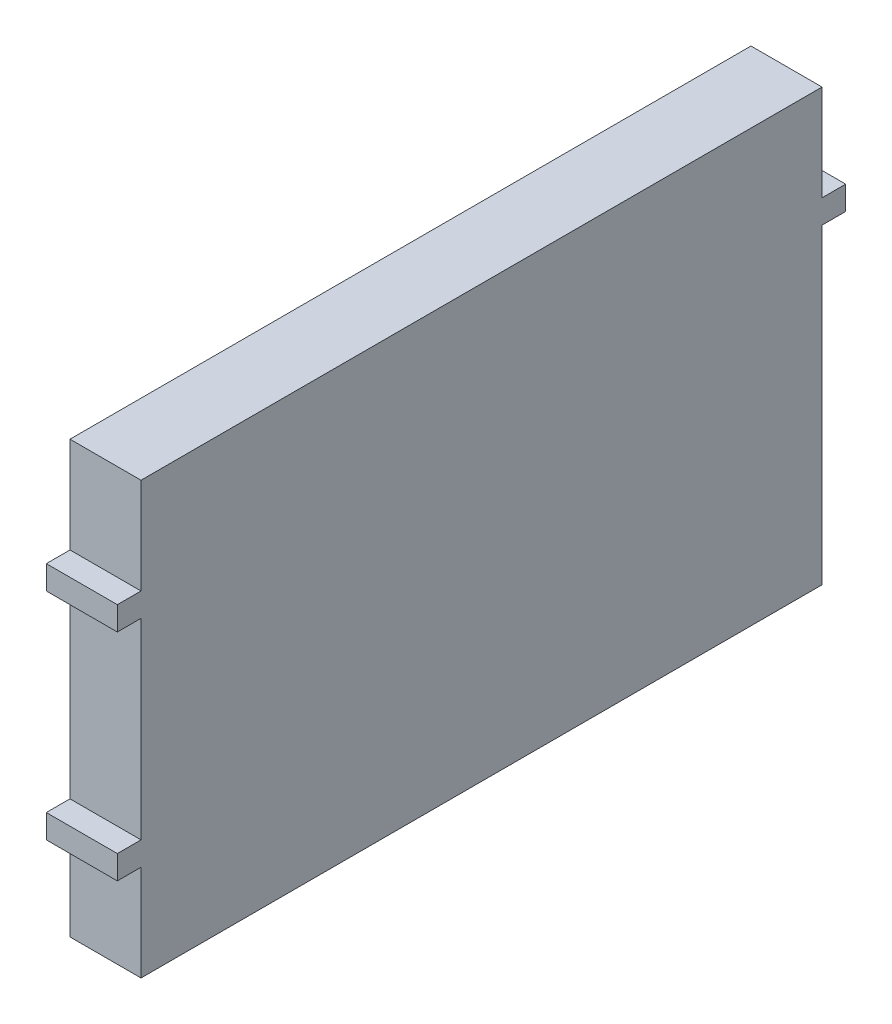
SolidWorks part; units mm, degrees
material "Balsa"
ref_plane "Front Plane" through (0, 0, 0) normal (0, 0, 1) x (1, 0, 0)
ref_plane "Top Plane" through (0, 0, 0) normal (0, 1, 0) x (1, 0, 0)
ref_plane "Right Plane" through (0, 0, 0) normal (1, 0, 0) x (0, 0, -1)
sketch "Sketch1" plane through (243.0177, 0, 0) normal (1, 0, 0) x (0, 0, -1)
  line L0 (-776.8812, 374.5917) -> (-773.7062, 374.5917) construction
  line L2 (-773.7062, 377.7667) -> (-776.8812, 377.7667) construction
  line L3 (-776.8812, 377.7667) -> (-776.8812, 374.5917) construction
  line L4 (-776.8812, 403.4842) -> (-773.7062, 403.4842) construction
  line L6 (-773.7062, 406.6592) -> (-776.8812, 406.6592) construction
  line L7 (-776.8812, 406.6592) -> (-776.8812, 403.4842) construction
  line L8 (-679.2499, 406.6592) -> (-682.4249, 406.6592) construction
  line L10 (-682.4249, 403.4842) -> (-679.2499, 403.4842) construction
  line L11 (-679.2499, 403.4842) -> (-679.2499, 406.6592) construction
  line L12 (-776.8812, 361.733) -> (-773.7062, 361.733) construction
  line L13 (-776.8812, 419.518) -> (-773.7062, 419.518) construction
  line L14 (-682.4249, 361.733) -> (-679.2499, 361.733) construction
  line L15 (-682.4249, 419.518) -> (-679.2499, 419.518) construction
  line L16 (-776.8812, 374.5917) -> (-773.7062, 374.5917)
  line L18 (-773.7062, 377.7667) -> (-776.8812, 377.7667)
  line L19 (-776.8812, 377.7667) -> (-776.8812, 374.5917)
  line L20 (-776.8812, 403.4842) -> (-773.7062, 403.4842)
  line L22 (-773.7062, 406.6592) -> (-776.8812, 406.6592)
  line L23 (-776.8812, 406.6592) -> (-776.8812, 403.4842)
  line L24 (-679.2499, 406.6592) -> (-682.4249, 406.6592)
  line L26 (-682.4249, 403.4842) -> (-679.2499, 403.4842)
  line L27 (-679.2499, 403.4842) -> (-679.2499, 406.6592)
  line L28 (-776.8812, 361.733) -> (-773.7062, 361.733) construction
  line L29 (-776.8812, 419.518) -> (-773.7062, 419.518) construction
  line L30 (-682.4249, 361.733) -> (-679.2499, 361.733) construction
  line L31 (-682.4249, 419.518) -> (-679.2499, 419.518) construction
  line L32 (-773.7062, 406.6592) -> (-773.7062, 419.518)
  line L33 (-773.7062, 419.518) -> (-682.4249, 419.518)
  line L34 (-682.4249, 419.518) -> (-682.4249, 406.6592)
  line L35 (-682.4249, 403.4842) -> (-682.4249, 361.733)
  line L36 (-682.4249, 361.733) -> (-773.7062, 361.733)
  line L37 (-773.7062, 361.733) -> (-773.7062, 374.5917)
  line L38 (-773.7062, 377.7667) -> (-773.7062, 403.4842)
extrude "Boss-Extrude1" add sketch "Sketch1" along normal up to surface (9.525 mm away)
